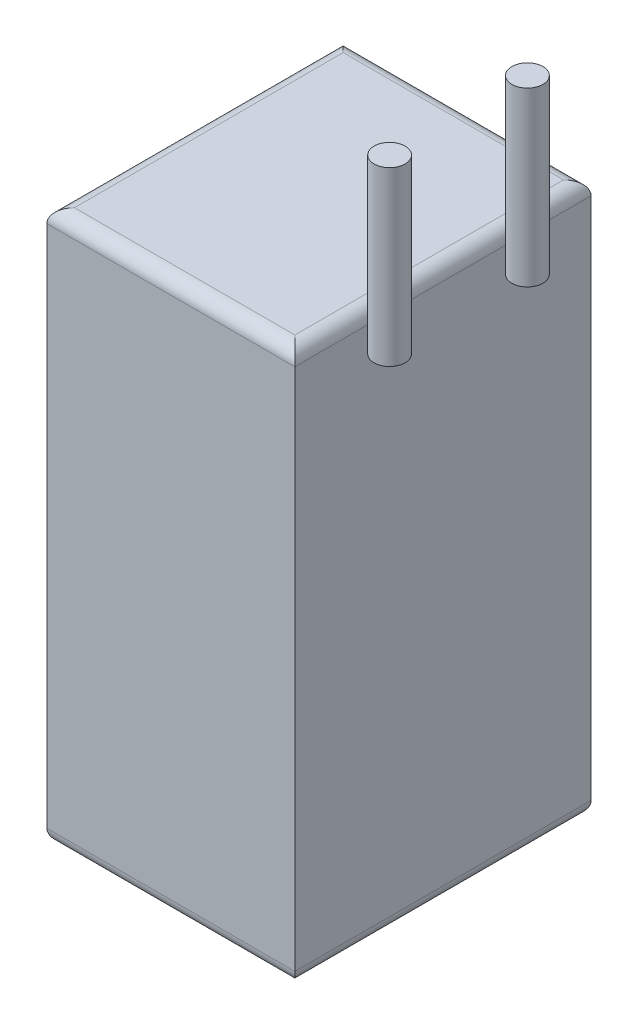
SolidWorks part; units mm, degrees
ref_plane "Front Plane" through (0, 0, 0) normal (0, 0, 1) x (1, 0, 0)
ref_plane "Top Plane" through (0, 0, 0) normal (0, 1, 0) x (1, 0, 0)
ref_plane "Right Plane" through (0, 0, 0) normal (1, 0, 0) x (0, 0, -1)
sketch "Sketch1" plane through (0, 0, 0) normal (0, 1, 0) x (1, 0, 0)
  line L1 (-18, 21.5) -> (18, 21.5)
  line L2 (-18, 21.5) -> (-18, -21.5)
  line L3 (-18, -21.5) -> (18, -21.5)
  line L4 (18, 21.5) -> (18, -21.5)
  line L5 (-18, 21.5) -> (18, -21.5) construction
  line L6 (-18, -21.5) -> (18, 21.5) construction
  point P0 (0, 0)
  dimension "D1" = 36
  dimension "D2" = 43
extrude "Boss-Extrude1" add sketch "Sketch1" along normal blind 80
sketch "Sketch2" plane through (0, 80, 0) normal (0, 1, 0) x (1, 0, 0)
  line L0 (0, 0) -> (29.1838, 0) construction
  line L1 (18, -21.5) -> (18, 21.5) construction
  circle A0 centre (20.25, 10) radius 2.25
  circle A1 centre (20.25, -10) radius 2.25
  dimension "D1" = 4.5
  dimension "D2" = 20
extrude "Boss-Extrude2" add sketch "Sketch2" along normal blind 20 and the other way blind 5 separate body
fillet "Fillet1" radius 2 8 edges at (0, 80, 21.5) (-18, 80, 0) (0, 80, -21.5) (18, 80, 0) (0, 0, -21.5) (-18, 0, 0) (0, 0, 21.5) (18, 0, 0)
